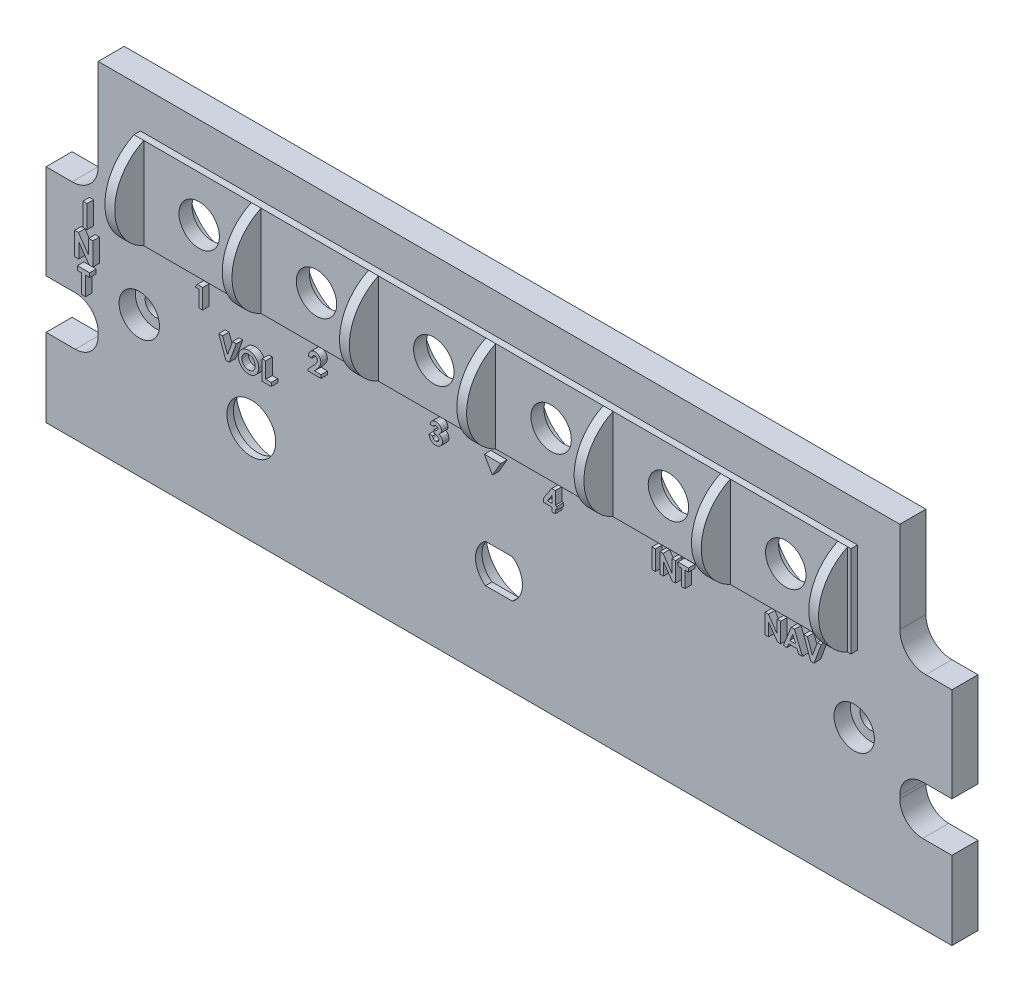
SolidWorks part; units mm, degrees
ref_plane "Front Plane" through (0, 0, 0) normal (0, 0, 1) x (1, 0, 0)
ref_plane "Top Plane" through (0, 0, 0) normal (0, 1, 0) x (1, 0, 0)
ref_plane "Right Plane" through (0, 0, 0) normal (1, 0, 0) x (0, 0, -1)
sketch "Sketch1" plane through (0, 0, 0) normal (0, 0, 1) x (1, 0, 0)
  line L1 (0, 0) -> (139, 0)
  line L2 (0, 0) -> (0, 12)
  line L3 (8, 52) -> (131, 52)
  line L4 (139, 0) -> (139, 12)
  line L5 (69.5, 52) -> (69.5, 0) construction
  line L6 (8, 52) -> (8, 0) construction
  line L11 (131, 52) -> (131, 0) construction
  line L21 (0, 19) -> (139, 19) construction
  line L22 (0, 0) -> (139, 0) construction
  line L23 (0, 0) -> (0, 12) construction
  line L25 (0, 52) -> (0, 64.6609) construction
  line L26 (8, 52) -> (8, 38)
  line L28 (0, 34) -> (4, 34)
  line L29 (8, 15.5) -> (8, 16)
  line L30 (4.5, 19.5) -> (0, 19.5)
  line L31 (0, 12) -> (4.5, 12)
  line L32 (0, 19.5) -> (0, 34)
  line L33 (0, 19.5) -> (0, 34) construction
  line L34 (139, 12) -> (134.5, 12)
  line L35 (134.5, 19.5) -> (139, 19.5)
  line L36 (131, 52) -> (131, 38)
  line L37 (139, 34) -> (135, 34)
  line L38 (139, 19.5) -> (139, 34)
  line L39 (131, 16) -> (131, 15.5)
  line L43 (67.4366, 12.05) -> (71.5634, 12.05)
  line L44 (71.5634, 17.95) -> (67.4366, 17.95)
  line L45 (67.4366, 12.05) -> (71.5634, 12.05)
  line L46 (71.5634, 17.95) -> (67.4366, 17.95)
  circle A14 centre (135, 16) radius 1.6 construction
  circle A15 centre (135, 38) radius 1.6 construction
  circle A16 centre (4, 16) radius 1.6 construction
  circle A17 centre (4, 38) radius 1.6 construction
  circle A18 centre (135, 16) radius 1.6 construction
  circle A19 centre (135, 38) radius 1.6 construction
  circle A26 centre (14.3091, 21.5) radius 1.6 construction
  circle A27 centre (124, 21.5) radius 1.6 construction
  circle A28 centre (114.5, 39) radius 3.1 construction
  circle A29 centre (31.5, 15) radius 3.75 construction
  circle A31 centre (96.5, 39) radius 3.1 construction
  circle A32 centre (78.5, 39) radius 3.1 construction
  circle A33 centre (60.5, 39) radius 3.1 construction
  circle A34 centre (42.5, 39) radius 3.1 construction
  circle A35 centre (24.5, 39) radius 3.1 construction
  circle A36 centre (14.3091, 21.5) radius 1.6
  circle A37 centre (124, 21.5) radius 1.6
  circle A38 centre (114.5, 39) radius 3.1
  circle A39 centre (31.5, 15) radius 3.75
  circle A41 centre (96.5, 39) radius 3.1
  circle A42 centre (78.5, 39) radius 3.1
  circle A43 centre (60.5, 39) radius 3.1
  circle A44 centre (42.5, 39) radius 3.1
  circle A45 centre (24.5, 39) radius 3.1
  circle A46 centre (4, 16) radius 1.6 construction
  circle A47 centre (4, 38) radius 1.6 construction
  arc A49 (8, 38) -> (4, 34) centre (4, 38) cw
  arc A50 (8, 16) -> (4.5, 19.5) centre (4.5, 16) ccw
  arc A51 (4.5, 12) -> (8, 15.5) centre (4.5, 15.5) ccw
  arc A52 (134.5, 12) -> (131, 15.5) centre (134.5, 15.5) cw
  arc A53 (131, 16) -> (134.5, 19.5) centre (134.5, 16) cw
  arc A54 (131, 38) -> (135, 34) centre (135, 38) ccw
  arc A57 (71.5634, 12.05) -> (71.5634, 17.95) centre (69.5, 15) ccw
  arc A58 (67.4366, 17.95) -> (67.4366, 12.05) centre (69.5, 15) ccw
  arc A59 (71.5634, 12.05) -> (71.5634, 17.95) centre (69.5, 15) ccw
  arc A60 (67.4366, 17.95) -> (67.4366, 12.05) centre (69.5, 15) ccw
  point P22 (8, 34)
  point P67 (8, 19.5)
  dimension "D3" = 139
  dimension "D4" = 8
  dimension "D5" = 18
  dimension "D8" = 4
  dimension "D12" = 22
  dimension "D13" = 0
  dimension "D6" = 4
  dimension "D10" = 3.5
  dimension "D11" = 3.5
  dimension "D1" = 123
  dimension "D7" = 3.5
  dimension "D20" = 52
  dimension "D9" = 4
extrude "Extrusion base" add sketch "Sketch1" along normal blind 4
sketch "Sketch6" plane through (0, 0, 0) normal (0, 0, -1) x (-1, 0, 0)
  circle A0 centre (-24.5, 39) radius 6.7
  circle A1 centre (-31.5, 15) radius 3.75 construction
  circle A2 centre (-24.5, 39) radius 3.1 construction
  circle A3 centre (-42.5, 39) radius 3.1 construction
  circle A4 centre (-60.5, 39) radius 3.1 construction
  circle A5 centre (-78.5, 39) radius 3.1 construction
  circle A6 centre (-96.5, 39) radius 3.1 construction
  circle A7 centre (-114.5, 39) radius 3.1 construction
  circle A9 centre (-31.5, 15) radius 3.75 construction
  circle A10 centre (-24.5, 39) radius 3.1 construction
  circle A11 centre (-42.5, 39) radius 3.1 construction
  circle A12 centre (-60.5, 39) radius 3.1 construction
  circle A13 centre (-78.5, 39) radius 3.1 construction
  circle A14 centre (-96.5, 39) radius 3.1 construction
  circle A15 centre (-114.5, 39) radius 3.1 construction
  arc A24 (-67.4366, 12.05) -> (-67.4366, 17.95) centre (-69.5, 15) ccw construction
  circle A25 centre (-69.5, 15) radius 3.6 construction
  circle A26 centre (-69.5, 15) radius 6
  circle A27 centre (-42.5, 39) radius 6.7
  circle A28 centre (-60.5, 39) radius 6.7
  circle A29 centre (-78.5, 39) radius 6.7
  circle A30 centre (-96.5, 39) radius 6.7
  circle A31 centre (-114.5, 39) radius 6.7
  circle A32 centre (-31.5, 15) radius 6.35
  dimension "D4" = 13.4
  dimension "D1" = 12.7
  dimension "D2" = 2.4
  dimension "D3" = 3.6
extrude "Back holes" cut sketch "Sketch6" against normal blind 3
sketch "Sketch7" plane through (0, 0, 4) normal (0, 0, 1) x (1, 0, 0)
  line L1 (14.5, 46) -> (124.5, 46)
  line L2 (14.5, 46) -> (14.5, 32)
  line L3 (14.5, 32) -> (124.5, 32)
  line L4 (124.5, 46) -> (124.5, 32)
  circle A0 centre (114.5, 39) radius 3.1 construction
  circle A1 centre (96.5, 39) radius 3.1 construction
  circle A2 centre (78.5, 39) radius 3.1 construction
  circle A3 centre (60.5, 39) radius 3.1 construction
  circle A4 centre (42.5, 39) radius 3.1 construction
  circle A5 centre (24.5, 39) radius 3.1 construction
  circle A6 centre (114.5, 39) radius 3.1
  circle A7 centre (96.5, 39) radius 3.1
  circle A8 centre (78.5, 39) radius 3.1
  circle A9 centre (60.5, 39) radius 3.1
  circle A10 centre (42.5, 39) radius 3.1
  circle A11 centre (24.5, 39) radius 3.1
  dimension "D1" = 110
  dimension "D2" = 14
  dimension "D3" = 7
  dimension "D4" = 10
extrude "Base suiches" add sketch "Sketch7" along normal blind 1
sketch "Sketch10" plane through (0, 0, 4) normal (0, 0, 1) x (1, 0, 0)
  circle A0 centre (124, 21.5) radius 3.1
  circle A1 centre (14.3091, 21.5) radius 3.1
  circle A2 centre (14.3091, 21.5) radius 1.6 construction
  dimension "D1" = 1.5
extrude "Cama tornillos" cut sketch "Sketch10" against normal blind 2.5
ref_plane "Plane1" through (14.5, 0, 0) normal (-1, 0, 0) x (0, 0, 1)
sketch "Sketch9" plane through (14.5, 0, 0) normal (-1, 0, 0) x (0, 0, 1)
  line L0 (5, 46) -> (5, 32) construction
  line L1 (5, 46) -> (5, 32)
  arc A0 (5, 46) -> (5, 32) centre (1.7441, 39) cw
extrude "Separador Suiches" add sketch "Sketch9" against normal blind 1.5 contours A0 L1
pattern_linear "LPattern1" count 7 spacing 18 along (1, 0, 0) of "Separador Suiches"
sketch "Sketch4" plane through (0, 0, 4) normal (0, 0, 1) x (1, 0, 0)
  line L0 (8, 26.9631) -> (8, 14.5758) construction
  line L2 (14.9935, 27.9665) -> (130.4748, 27.9665) construction
  line L3 (-3.8412, 29.7606) -> (13.9628, 29.7606) construction
  line L4 (-4.2039, 25.2606) -> (13.9628, 25.2606) construction
  line L5 (-4.2039, 20.7606) -> (14.2039, 20.7606) construction
  line L6 (5, 33.1522) -> (5, -6.1206) construction
  line L8 (69.5, 28.2679) -> (70.75, 30.433)
  line L9 (70.75, 30.433) -> (68.25, 30.433)
  line L10 (68.25, 30.433) -> (69.5, 28.2679)
  circle A0 centre (69.5, 29.7113) radius 0.7217 construction
  circle A1 centre (69.5, 14.7113) radius 3.75 construction
  text T0 "<b> I</b>" font "Century Gothic" height 3.5
  text T1 "<b>1</b>" font "Century Gothic" height 3
  text T2 "<b>2</b>" font "Century Gothic" height 3
  text T3 "<b>3</b>" font "Century Gothic" height 3
  text T4 "<b>VOL</b>" font "Century Gothic" height 3
  text T5 "<b>NAV</b>" font "Century Gothic" height 3
  text T6 "INT" font "Century Gothic" height 3
  text T7 "N" font "Century Gothic" height 3.5
  text T8 " T" font "Century Gothic" height 3.5
  text T9 "<b>4</b>" font "Century Gothic" height 3
  dimension "D1" = 4.5
  dimension "D2" = 4.5
  dimension "D3" = 3
  dimension "D4" = 2.5
  dimension "D5" = 15
extrude "Textos" add sketch "Sketch4" along normal blind 1
